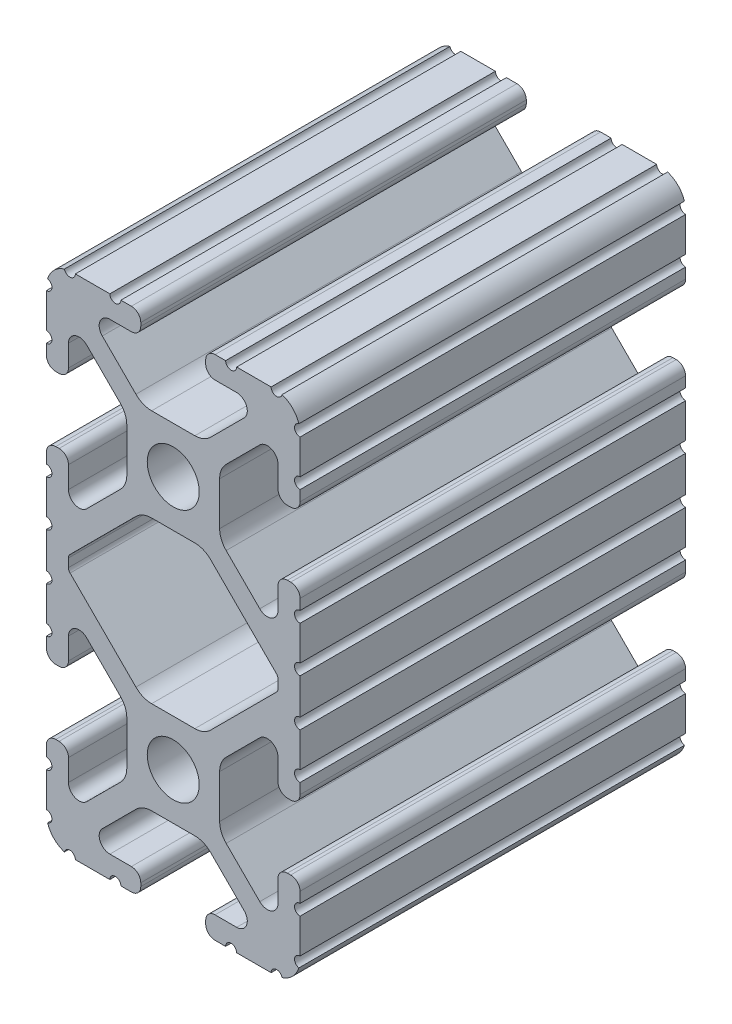
SolidWorks part; units mm, degrees
ref_plane "Front Plane" through (0, 0, 0) normal (0, 0, 1) x (1, 0, 0)
ref_plane "Top Plane" through (0, 0, 0) normal (0, 1, 0) x (1, 0, 0)
ref_plane "Right Plane" through (0, 0, 0) normal (1, 0, 0) x (0, 0, -1)
sketch "Sketch2" plane through (0, 0, 0) normal (0, 0, 1) x (1, 0, 0)
  line L0 (0, 25.4) -> (0, -25.4) construction
  line L1 (-12.7, 0) -> (12.7, 0) construction
  line L2 (3.2512, -25.4) -> (12.7, -25.4)
  line L3 (12.7, -25.4) -> (12.7, -15.9512)
  line L4 (3.2512, -25.4) -> (3.2512, -23.1902)
  line L5 (3.2512, -23.1902) -> (8.9276, -23.1902)
  line L6 (8.9276, -23.1902) -> (3.0856, -17.3482)
  line L7 (0, -12.7) -> (12.7, -25.4) construction
  line L8 (12.7, -15.9512) -> (10.4902, -15.9512)
  line L9 (10.4902, -15.9512) -> (10.4902, -21.6276)
  line L10 (10.4902, -21.6276) -> (4.6482, -15.7856)
  circle A0 centre (0, -12.7) radius 2.6035
  arc A1 (6.3485, -23.1902) -> (7.1039, -21.3665) centre (6.3485, -22.1219) ccw construction
  point P8 (0, -17.3482)
  dimension "Center Hole Diameter" = 5.207
  dimension "Rail Height" = 50.8
  dimension "Rail Width" = 25.4
  dimension "T-Slot Width" = 6.5024
  dimension "Slot Inner Width" = 14.8336
  dimension "Thickness" = 2.2098
  dimension "Slot Depth" = 5.842
  dimension "D1" = 2.2098
  dimension "C to C" = 25.4
sketch "Sketch3" plane through (0, 0, 0) normal (1, 0, 0) x (0, 0, -1)
  line L0 (-76.2, -25.4) -> (76.2, -25.4) construction
  line L1 (-50.8, 0) -> (50.8, 0) construction
  dimension "Length" = 152.4
  dimension "D1" = 25.4
sketch "Sketch4" plane through (0, 0, 0) normal (0, 0, 1) x (1, 0, 0)
  line L0 (4.1904, -25.4) -> (10.1173, -25.4)
  line L1 (3.2512, -25.4) -> (12.7, -25.4) construction
  line L2 (3.2512, -25.4) -> (3.2512, -23.1902) construction
  line L3 (3.2512, -23.1902) -> (8.9276, -23.1902) construction
  line L4 (3.2512, -24.1294) -> (3.2512, -24.4608)
  line L5 (4.1904, -23.1902) -> (6.3485, -23.1902)
  line L6 (0, -17.3482) -> (2.164, -17.3482)
  line L7 (8.9276, -23.1902) -> (3.0856, -17.3482) construction
  line L8 (3.7373, -17.9999) -> (7.1039, -21.3665)
  line L9 (12.7, -25.4) -> (12.7, -15.9512) construction
  line L10 (10.4902, -21.6276) -> (4.6482, -15.7856) construction
  line L11 (10.4902, -15.9512) -> (10.4902, -21.6276) construction
  line L12 (10.4902, -19.0485) -> (10.4902, -16.8904)
  line L13 (12.7, -15.9512) -> (10.4902, -15.9512) construction
  line L14 (11.4294, -15.9512) -> (11.7608, -15.9512)
  line L15 (12.7, -16.8904) -> (12.7, -22.8173)
  line L16 (8.6665, -19.8039) -> (5.2999, -16.4373)
  line L17 (4.6482, -12.7) -> (4.6482, -14.864)
  line L19 (0, -17.3482) -> (0, -15.3035)
  line L20 (0, 25.4) -> (0, -25.4) construction
  line L21 (4.6482, -12.7) -> (2.6035, -12.7)
  arc A0 (3.2512, -24.4608) -> (4.1904, -25.4) centre (4.1904, -24.4608) ccw
  circle A1 centre (0, -12.7) radius 2.6035 construction
  arc A2 (3.2512, -24.1294) -> (4.1904, -23.1902) centre (4.1904, -24.1294) cw
  arc A3 (6.3485, -23.1902) -> (7.1039, -21.3665) centre (6.3485, -22.1219) ccw
  arc A4 (2.164, -17.3482) -> (3.7373, -17.9999) centre (2.164, -19.5732) cw
  arc A5 (10.1173, -25.4) -> (12.7, -22.8173) centre (10.1173, -22.8173) ccw
  arc A6 (8.6665, -19.8039) -> (10.4902, -19.0485) centre (9.4219, -19.0485) ccw
  arc A7 (10.4902, -16.8904) -> (11.4294, -15.9512) centre (11.4294, -16.8904) cw
  arc A8 (11.7608, -15.9512) -> (12.7, -16.8904) centre (11.7608, -16.8904) cw
  arc A9 (5.2999, -16.4373) -> (4.6482, -14.864) centre (6.8732, -14.864) cw
  arc A11 (0, -15.3035) -> (2.6035, -12.7) centre (0, -12.7) ccw
  dimension "D1" = 2.5827
  dimension "D2" = 2.225
  dimension "D3" = 0.9392
extrude "Boss-Extrude1" add sketch "Sketch4" along normal mid plane 152.4
sketch "Sketch5" plane through (0, 0, 0) normal (0, 0, 1) x (1, 0, 0)
  line L0 (3.2512, -25.4) -> (12.7, -25.4) construction
  line L1 (4.1904, -23.1902) -> (6.3485, -23.1902) construction
  line L3 (0, -12.7) -> (12.7, -25.4) construction
  line L4 (6.3485, -23.1902) -> (6.3485, -25.4) construction
  line L5 (8.9276, -23.1902) -> (3.0856, -17.3482) construction
  circle A0 centre (10.3562, -25.4) radius 0.5524
  circle A1 centre (5.796, -25.4) radius 0.5524
  circle A2 centre (12.7, -23.0562) radius 0.5524
  circle A3 centre (12.7, -18.496) radius 0.5524
  point P10 (5.2694, -23.1902)
  point P12 (9.4219, -19.0485)
  dimension "D1" = 1.1049
extrude "Cut-Extrude1" cut sketch "Sketch5" against normal through all both and the other way through all
mirror "Mirror1" about plane through (4.6482, -12.7, 76.2) normal (0, -1, 0) of bodies 137 134
sketch "Sketch6" plane through (0, 0, 0) normal (0, 0, 1) x (1, 0, 0)
  line L0 (12.7, -1.7914) -> (12.7, 0)
  line L1 (12.7, 0) -> (9.8037, 0)
  line L2 (-12.7, 0) -> (12.7, 0) construction
  line L3 (9.8037, 0) -> (9.8037, -2.3438)
  line L4 (9.8037, -2.3438) -> (12.1476, -2.3438)
  circle A0 centre (12.7, -2.3438) radius 0.5524 construction
  arc A1 (12.7, -1.7914) -> (12.1476, -2.3438) centre (12.7, -2.3438) ccw
  arc A4 (12.58, -1.8046) -> (12.7, -2.8963) centre (12.7, -2.3438) ccw construction
  arc A6 (9.8037, 0) -> (10.8954, -0.12) centre (10.3562, 0) ccw construction
extrude "Boss-Extrude2" add sketch "Sketch6" along normal mid plane 152.4
sketch "Sketch7" plane through (0, 0, 0) normal (0, 0, 1) x (1, 0, 0)
  line L0 (5.4206, -5.7168) -> (10.3284, -0.809)
  line L1 (3.7373, -7.4001) -> (7.1039, -4.0335) construction
  line L2 (10.4902, -0.4184) -> (10.4902, 0)
  line L3 (0, 0) -> (10.4902, 0)
  line L4 (-12.7, 0) -> (12.7, 0) construction
  line L5 (0, 0) -> (5.4206, -5.7168)
  arc A0 (10.3284, -0.809) -> (10.4902, -0.4184) centre (9.9377, -0.4184) ccw
  arc A3 (12.7, -1.7914) -> (12.7, -2.8963) centre (12.7, -2.3438) ccw construction
extrude "Cut-Extrude2" cut sketch "Sketch7" against normal through all both and the other way through all
mirror "Mirror2" about plane through (0, 0, 0) normal (0, 1, 0) of bodies 139 135
mirror "Mirror3" about plane through (0, 0, 0) normal (1, 0, 0) of bodies 136
sketch "Sketch8" plane through (0, 0, -76.2) normal (0, 0, -1) x (-1, 0, 0)
  line L1 (-24.2228, 32.1699) -> (24.2228, 32.1699)
  line L2 (-24.2228, 32.1699) -> (-24.2228, -32.1699)
  line L3 (-24.2228, -32.1699) -> (24.2228, -32.1699)
  line L4 (24.2228, 32.1699) -> (24.2228, -32.1699)
  line L5 (-24.2228, 32.1699) -> (24.2228, -32.1699) construction
  line L6 (-24.2228, -32.1699) -> (24.2228, 32.1699) construction
  point P0 (0, 0)
extrude "Cut-Extrude3" cut sketch "Sketch8" against normal blind 113.792
equation "\"D1@Boss-Extrude1\"=\"Length@Sketch3\""
equation "\"D1@Sketch2\"=\"Thickness@Sketch2\""
equation "\"D2@Sketch4\"=\"Slot Inner Width@Sketch2\"*0.15"
equation "\"D1@Sketch4\"=\"D3@Sketch4\"*2.75"
equation "\"D3@Sketch4\"=\"Thickness@Sketch2\"*0.425"
equation "\"D1@Sketch5\"=\"Thickness@Sketch2\"*0.5"
equation "\"D1@Boss-Extrude2\"=\"Length@Sketch3\""
